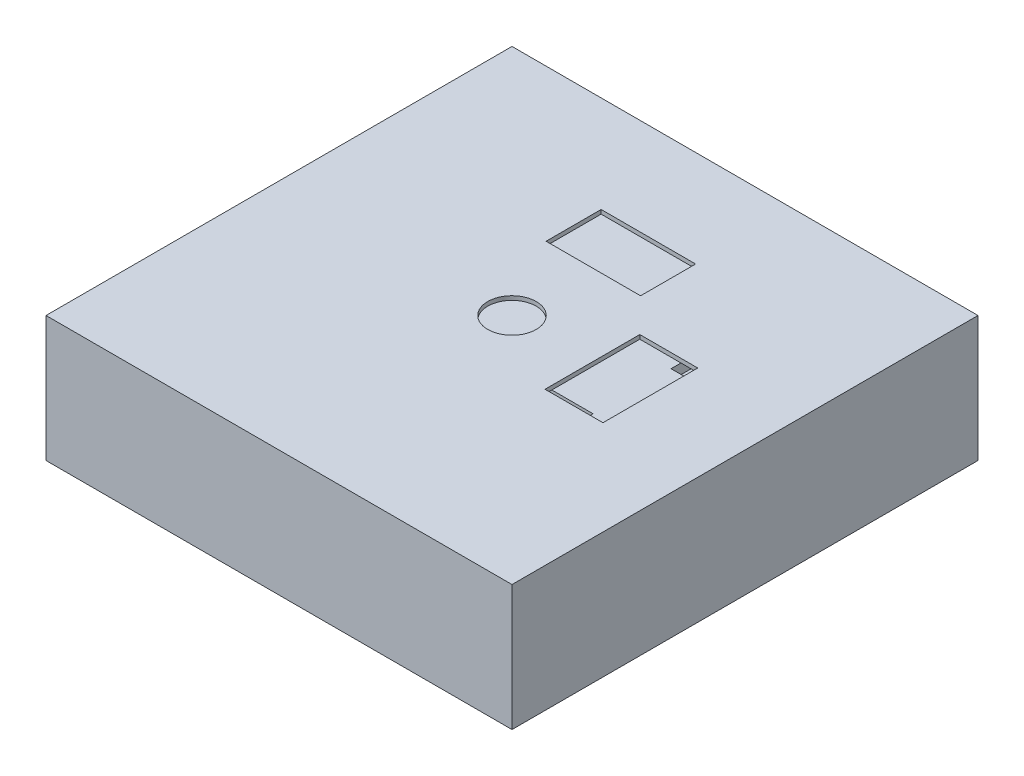
SolidWorks part; units mm, degrees
ref_plane "Alzado" through (0, 0, 0) normal (0, 0, 1) x (1, 0, 0)
ref_plane "Planta" through (0, 0, 0) normal (0, 1, 0) x (1, 0, 0)
ref_plane "Vista lateral" through (0, 0, 0) normal (1, 0, 0) x (0, 0, -1)
sketch "Croquis1" plane through (0, 0, 0) normal (0, 1, 0) x (1, 0, 0)
  line L1 (-125, 125) -> (125, 125)
  line L2 (-125, 125) -> (-125, -125)
  line L3 (-125, -125) -> (125, -125)
  line L4 (125, 125) -> (125, -125)
  line L5 (-125, 125) -> (125, -125) construction
  line L6 (-125, -125) -> (125, 125) construction
  point P0 (0, 0)
  dimension "D1" = 250
  dimension "D2" = 250
extrude "Saliente-Extruir1" add sketch "Croquis1" along normal blind 20
sketch "Croquis2" plane through (0, 20, 0) normal (0, 1, 0) x (1, 0, 0)
  line L0 (125, 125) -> (-125, 125) construction
  line L1 (20, 88.5) -> (35, 88.5)
  line L2 (20, 88.5) -> (20, 58.5)
  line L3 (20, 58.5) -> (35, 58.5)
  line L4 (35, 88.5) -> (35, 58.5)
  line L5 (58.5, -20) -> (88.5, -20)
  line L6 (58.5, -20) -> (58.5, -35)
  line L7 (58.5, -35) -> (88.5, -35)
  line L8 (88.5, -20) -> (88.5, -35)
  line L9 (-20, 20) -> (20, 20)
  line L10 (-20, 20) -> (-20, -20)
  line L11 (-20, -20) -> (20, -20)
  line L12 (20, 20) -> (20, -20)
  line L13 (125, -125) -> (125, 125) construction
  line L14 (-125, -125) -> (125, -125) construction
  line L15 (-125, 125) -> (-125, -125) construction
  dimension "D1" = 15
  dimension "D2" = 30
  dimension "D3" = 30
  dimension "D4" = 15
  dimension "D5" = 40
  dimension "D6" = 40
  dimension "D7" = 36.5
  dimension "D8" = 90
  dimension "D9" = 36.5
  dimension "D10" = 90
  dimension "D11" = 105
  dimension "D12" = 105
extrude "Cortar-Extruir1" cut sketch "Croquis2" against normal blind 5
sketch "Croquis3" plane through (0, 20, 0) normal (0, 1, 0) x (1, 0, 0)
  line L1 (-125, 125) -> (125, 125)
  line L2 (-125, 125) -> (-125, -125)
  line L3 (-125, -125) -> (125, -125)
  line L4 (125, 125) -> (125, -125)
  line L5 (-100, 100) -> (100, 100)
  line L6 (-100, 100) -> (-100, -100)
  line L7 (-100, -100) -> (100, -100)
  line L8 (100, 100) -> (100, -100)
  line L9 (-100, 100) -> (100, -100) construction
  line L10 (-100, -100) -> (100, 100) construction
  point P6 (0, 0)
  dimension "D1" = 200
  dimension "D2" = 200
extrude "Cortar-Extruir2" cut sketch "Croquis3" against normal blind 20
sketch "Croquis4" plane through (0, 0, 0) normal (0, -1, 0) x (1, 0, 0)
  line L0 (100, -100) -> (-100, -100) construction
  line L2 (100, 100) -> (100, -99.9964)
  line L4 (115, 96.3359) -> (115, -96.5002)
  line L5 (-100, 100) -> (100, 100)
  line L7 (-100, 115) -> (115, 115)
  line L8 (115, 96.3359) -> (115, 115)
  line L10 (-100, -100) -> (-100, 100)
  line L11 (-100, 115) -> (-115, 115)
  line L12 (-115, -98.6641) -> (-115, 115)
  line L14 (-115, -98.6641) -> (-115, -115)
  line L15 (-115, -115) -> (115, -115)
  line L16 (115, -96.5002) -> (115, -115)
  line M9 (100, -100) -> (100, 100)
  line M10 (100, 100) -> (-100, 100)
  line M11 (-100, 100) -> (-100, -100)
  line M12 (-100, -100) -> (100, -100)
  dimension "D1" = 15
  dimension "D2" = 15
  dimension "D3" = 15
  dimension "D4" = 15
extrude "Saliente-Extruir2" add sketch "Croquis4" against normal blind 20 contours L16 L4 L8 L7 L11 L12 L14 L15 M9 M12 M11 M10
sketch "Croquis5" plane through (0, 20, 0) normal (0, 1, 0) x (1, 0, 0)
  line L0 (115, -115) -> (115, 115) construction
  line L1 (-115, 115) -> (115, 115)
  line L2 (-115, 115) -> (-115, 110.2412)
  line L3 (-110, 110) -> (110, 110)
  line L4 (115, 115) -> (115, 110.2412)
  line L5 (-115, 115) -> (-115, -115) construction
  line L6 (115, -115) -> (-115, -115)
  line L7 (115, -115) -> (115, -107.3273)
  line L8 (110, -110) -> (-110, -110)
  line L9 (-115, -115) -> (-115, -107.3273)
  line L11 (-115, -115) -> (-108.2986, -115)
  line L12 (-115, -115) -> (-115, 110.2412)
  line L14 (-110, -110) -> (-110, 110)
  line L16 (115, -107.3273) -> (115, 110.2412)
  line L18 (110, -110) -> (110, 110)
  line M21 (115, -115) -> (115, 115)
  line M22 (115, 115) -> (-115, 115)
  line M23 (-115, 115) -> (-115, -115)
  line M24 (-115, -115) -> (115, -115)
  dimension "D1" = 5
  dimension "D2" = 5
  dimension "D3" = 5
  dimension "D4" = 5
extrude "Saliente-Extruir3" add sketch "Croquis5" along normal blind 40 contours L6 L18 L8 L14 L3 M24 M21 M22 M23
sketch "Croquis6" plane through (0, 60, 0) normal (0, 1, 0) x (1, 0, 0)
  line L1 (-115, 115) -> (115, 115)
  line L2 (-115, 115) -> (-115, -115)
  line L3 (-115, -115) -> (115, -115)
  line L4 (115, 115) -> (115, -115)
extrude "Saliente-Extruir4" add sketch "Croquis6" along normal blind 2
sketch "Croquis8" plane through (0, 62, 0) normal (0, 1, 0) x (1, 0, 0)
  line L27 (39.6863, 23.3917) -> (68.2858, 23.3917)
  line L28 (39.6863, 23.3917) -> (39.6863, -23.3917)
  line L29 (39.6863, -23.3917) -> (68.2858, -23.3917)
  line L30 (68.2858, 23.3917) -> (68.2858, -23.3917)
  line L31 (-23.3169, 40.1494) -> (23.3169, 40.1494)
  line L32 (-23.3169, 40.1494) -> (-23.3169, 67.3087)
  line L33 (-23.3169, 67.3087) -> (23.3169, 67.3087)
  line L34 (23.3169, 40.1494) -> (23.3169, 67.3087)
  circle A0 centre (0, 0) radius 9.175
  point P4 (39.6863, 0)
  point P5 (0, 40.1494)
sketch "Croquis10" plane through (0, 62, 0) normal (0, 1, 0) x (1, 0, 0)
  circle A0 centre (0, 0) radius 11.9595
extrude "Cortar-Extruir5" cut sketch "Croquis8" against normal up to next
extrude "Cortar-Extruir4" cut sketch "Croquis10" against normal up to next
